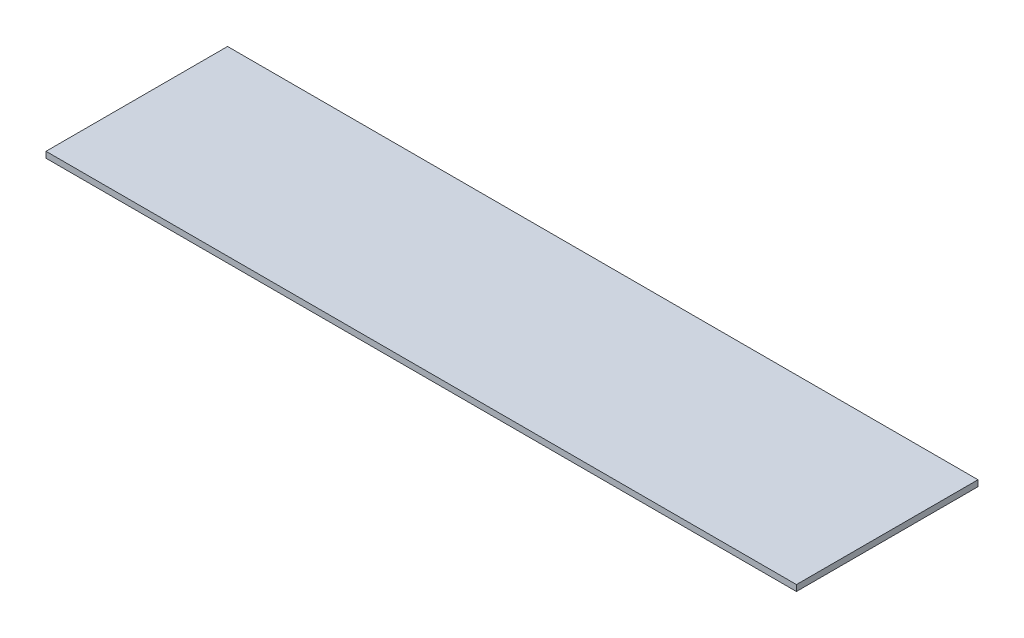
SolidWorks part; units mm, degrees
ref_plane "Front Plane" through (0, 0, 0) normal (0, 0, 1) x (1, 0, 0)
ref_plane "Top Plane" through (0, 0, 0) normal (0, 1, 0) x (1, 0, 0)
ref_plane "Right Plane" through (0, 0, 0) normal (1, 0, 0) x (0, 0, -1)
sketch "Sketch1" plane through (0, 0, 0) normal (0, 1, 0) x (1, 0, 0)
  line L1 (-393.7, -95.25) -> (393.7, -95.25)
  line L2 (-393.7, -95.25) -> (-393.7, 95.25)
  line L3 (-393.7, 95.25) -> (393.7, 95.25)
  line L4 (393.7, -95.25) -> (393.7, 95.25)
  line L5 (-393.7, -95.25) -> (393.7, 95.25) construction
  line L6 (-393.7, 95.25) -> (393.7, -95.25) construction
  point P0 (0, 0)
  dimension "D1" = 190.5
  dimension "D2" = 787.4
extrude "Boss-Extrude1" add sketch "Sketch1" along normal blind 6.35
